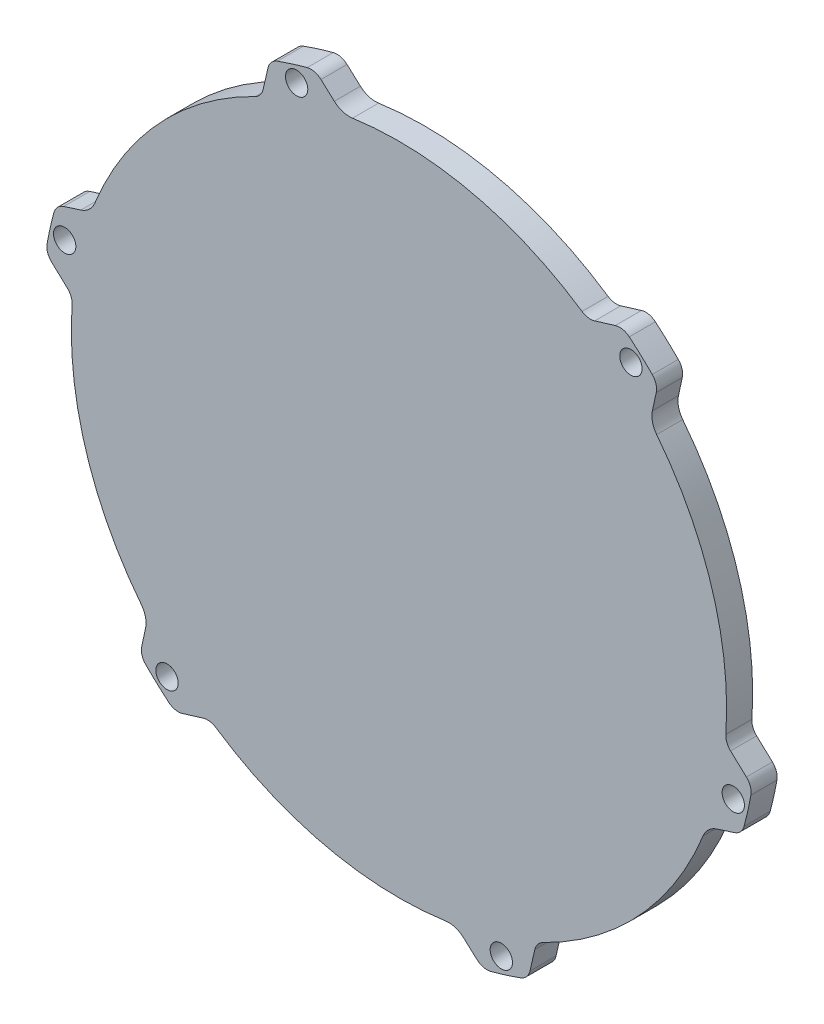
SolidWorks part; units mm, degrees
material "6063-O"
ref_plane "Front Plane" through (0, 0, 0) normal (0, 0, 1) x (1, 0, 0)
ref_plane "Top Plane" through (0, 0, 0) normal (0, 1, 0) x (1, 0, 0)
ref_plane "Right Plane" through (0, 0, 0) normal (1, 0, 0) x (0, 0, -1)
sketch "Sketch2" plane through (0, 0, 0) normal (0, 0, 1) x (1, 0, 0)
  line L0 (-44.8895, 10.0465) -> (-46.8412, 10.4833)
  line L1 (-45.0185, 13.8979) -> (-42.7088, 14.6367)
  line L2 (-46.6479, 6.6175) -> (-44.5268, 4.6417)
  line L4 (-10.4733, 45.9361) -> (-8.6786, 44.3053)
  line L5 (-17.593, 43.707) -> (-18.2436, 40.8822)
  line L7 (34.5452, 32.0382) -> (34.0302, 29.6686)
  line L8 (29.0549, 37.0895) -> (26.2833, 36.2405)
  line L10 (45.0185, -13.8979) -> (42.7088, -14.6367)
  line L11 (46.6479, -6.6175) -> (44.5268, -4.6417)
  line L13 (10.4733, -45.9361) -> (8.6786, -44.3053)
  line L14 (17.593, -43.707) -> (18.2436, -40.8822)
  line L16 (-34.5452, -32.0382) -> (-34.0302, -29.6686)
  line L17 (-29.0549, -37.0895) -> (-26.2833, -36.2405)
  line L18 (-13.7442, 43.8987) -> (-14.3418, 45.8073) [skipped]
  line L19 (31.1453, 33.8522) -> (32.4994, 35.324) [skipped]
  line L20 (44.8895, -10.0465) -> (46.8412, -10.4833) [skipped]
  line L21 (13.7442, -43.8987) -> (14.3418, -45.8073) [skipped]
  line L22 (-31.1453, -33.8522) -> (-32.4994, -35.324) [skipped]
  arc A0 (-46.3399, 12.5144) -> (-47.2535, 8.4323) centre (0, 0) ccw
  arc A1 (-43.8948, 3.0401) -> (-34.6025, -27.1784) centre (0, 0) ccw
  circle A2 centre (-13.7442, 43.8987) radius 1.5
  arc A3 (-40.8384, 16.3775) -> (-42.7088, 14.6367) centre (-43.6229, 17.4941) cw
  arc A4 (-46.6479, 6.6175) -> (-47.2535, 8.4323) centre (-45.2846, 8.081) cw
  arc A5 (-46.3399, 12.5144) -> (-45.0185, 13.8979) centre (-44.4091, 11.993) cw
  arc A6 (-43.8948, 3.0401) -> (-44.5268, 4.6417) centre (-45.8901, 3.1783) ccw
  arc A7 (-12.3322, 46.3888) -> (-16.3242, 45.1389) centre (0, 0) ccw
  arc A8 (-6.2359, 43.5559) -> (-8.6786, 44.3053) centre (-6.6611, 46.5256) cw
  arc A9 (-17.593, 43.707) -> (-16.3242, 45.1389) centre (-15.644, 43.2581) cw
  arc A10 (-12.3322, 46.3888) -> (-10.4733, 45.9361) centre (-11.8183, 44.4559) cw
  arc A11 (-19.3146, 39.5341) -> (-18.2436, 40.8822) centre (-20.1925, 41.3311) ccw
  arc A12 (34.0078, 33.8744) -> (30.9294, 36.7066) centre (0, 0) ccw
  arc A13 (34.6025, 27.1784) -> (34.0302, 29.6686) centre (36.9618, 29.0315) cw
  arc A14 (29.0549, 37.0895) -> (30.9294, 36.7066) centre (29.6406, 35.1772) cw
  arc A15 (34.0078, 33.8744) -> (34.5452, 32.0382) centre (32.5908, 32.4629) cw
  arc A16 (24.5802, 36.494) -> (26.2833, 36.2405) centre (25.6975, 38.1528) ccw
  arc A17 (46.3399, -12.5144) -> (47.2535, -8.4323) centre (0, 0) ccw
  arc A18 (40.8384, -16.3775) -> (42.7088, -14.6367) centre (43.6229, -17.4941) cw
  arc A19 (46.6479, -6.6175) -> (47.2535, -8.4323) centre (45.2846, -8.081) cw
  arc A20 (46.3399, -12.5144) -> (45.0185, -13.8979) centre (44.4091, -11.993) cw
  arc A21 (43.8948, -3.0401) -> (44.5268, -4.6417) centre (45.8901, -3.1783) ccw
  arc A22 (12.3322, -46.3888) -> (16.3242, -45.1389) centre (0, 0) ccw
  arc A23 (6.2359, -43.5559) -> (8.6786, -44.3053) centre (6.6611, -46.5256) cw
  arc A24 (17.593, -43.707) -> (16.3242, -45.1389) centre (15.644, -43.2581) cw
  arc A25 (12.3322, -46.3888) -> (10.4733, -45.9361) centre (11.8183, -44.4559) cw
  arc A26 (19.3146, -39.5341) -> (18.2436, -40.8822) centre (20.1925, -41.3311) ccw
  arc A27 (-34.0078, -33.8744) -> (-30.9294, -36.7066) centre (0, 0) ccw
  arc A28 (-34.6025, -27.1784) -> (-34.0302, -29.6686) centre (-36.9618, -29.0315) cw
  arc A29 (-29.0549, -37.0895) -> (-30.9294, -36.7066) centre (-29.6406, -35.1772) cw
  arc A30 (-34.0078, -33.8744) -> (-34.5452, -32.0382) centre (-32.5908, -32.4629) cw
  arc A31 (-24.5802, -36.494) -> (-26.2833, -36.2405) centre (-25.6975, -38.1528) ccw
  arc A32 (-19.3146, 39.5341) -> (-40.8384, 16.3775) centre (0, 0) ccw
  arc A33 (24.5802, 36.494) -> (-6.2359, 43.5559) centre (0, 0) ccw
  arc A34 (43.8948, -3.0401) -> (34.6025, 27.1784) centre (0, 0) ccw
  arc A35 (19.3146, -39.5341) -> (40.8384, -16.3775) centre (0, 0) ccw
  arc A36 (-24.5802, -36.494) -> (6.2359, -43.5559) centre (0, 0) ccw
  circle A37 centre (-44.8895, 10.0465) radius 1.5
  circle A38 centre (31.1453, 33.8522) radius 1.5
  circle A39 centre (44.8895, -10.0465) radius 1.5
  circle A40 centre (13.7442, -43.8987) radius 1.5
  circle A41 centre (-31.1453, -33.8522) radius 1.5
  circle A42 centre (0, 0) radius 42
  circle A43 centre (0, 0) radius 39.4
  point P15 (-41.3367, 15.0757)
  point P17 (-47.434, 7.3498)
  point P20 (-46.0417, 13.5706)
  point P23 (-43.8194, 3.9827)
  point P93 (0, 0)
  point P105 (0, 0)
  dimension "D1" = 96
  dimension "D2" = 88
  dimension "D3" = 3
  dimension "D4" = 2
  dimension "D5" = 2
  dimension "D7" = 6
  dimension "D8" = 2.6
  dimension "D6" = 6
extrude "Boss-Extrude1" add sketch "Sketch2" along normal blind 2
sketch "Sketch3" plane through (0, 0, 2) normal (0, 0, 1) x (1, 0, 0)
  line L10 (8.6786, -44.3053) -> (10.4733, -45.9361)
  line L12 (-46.6479, 6.6175) -> (-44.5268, 4.6417)
  line L13 (-34.0302, -29.6686) -> (-34.5452, -32.0382)
  line L14 (-29.0549, -37.0895) -> (-26.2833, -36.2405)
  line L15 (8.6786, -44.3053) -> (10.4733, -45.9361)
  line L19 (34.0302, 29.6686) -> (34.5452, 32.0382)
  line L20 (29.0549, 37.0895) -> (26.2833, 36.2405)
  line L21 (-8.6786, 44.3053) -> (-10.4733, 45.9361)
  line L22 (-17.593, 43.707) -> (-18.2436, 40.8822)
  line L23 (-42.7088, 14.6367) -> (-45.0185, 13.8979)
  line L24 (-46.6479, 6.6175) -> (-44.5268, 4.6417)
  line L25 (-34.0302, -29.6686) -> (-34.5452, -32.0382)
  line L26 (-29.0549, -37.0895) -> (-26.2833, -36.2405)
  line L31 (34.0302, 29.6686) -> (34.5452, 32.0382)
  line L32 (29.0549, 37.0895) -> (26.2833, 36.2405)
  line L33 (-8.6786, 44.3053) -> (-10.4733, 45.9361)
  line L34 (-17.593, 43.707) -> (-18.2436, 40.8822)
  line L35 (-42.7088, 14.6367) -> (-45.0185, 13.8979)
  line L36 (17.593, -43.707) -> (18.2436, -40.8822)
  line L37 (17.593, -43.707) -> (18.2436, -40.8822)
  line L38 (42.7088, -14.6367) -> (45.0185, -13.8979)
  line L39 (42.7088, -14.6367) -> (45.0185, -13.8979)
  line L40 (46.6479, -6.6175) -> (44.5268, -4.6417)
  line L41 (46.6479, -6.6175) -> (44.5268, -4.6417)
  arc A26 (8.6786, -44.3053) -> (6.2359, -43.5559) centre (6.6611, -46.5256) ccw
  arc A36 (-45.0185, 13.8979) -> (-46.3399, 12.5144) centre (-44.4091, 11.993) ccw
  arc A37 (-46.3399, 12.5144) -> (-47.2535, 8.4323) centre (0, 0) ccw
  arc A38 (-47.2535, 8.4323) -> (-46.6479, 6.6175) centre (-45.2846, 8.081) ccw
  arc A39 (-43.8948, 3.0401) -> (-44.5268, 4.6417) centre (-45.8901, 3.1783) ccw
  arc A40 (-43.8948, 3.0401) -> (-34.6025, -27.1784) centre (0, 0) ccw
  arc A41 (-34.0302, -29.6686) -> (-34.6025, -27.1784) centre (-36.9618, -29.0315) ccw
  arc A42 (-34.5452, -32.0382) -> (-34.0078, -33.8744) centre (-32.5908, -32.4629) ccw
  arc A43 (-34.0078, -33.8744) -> (-30.9294, -36.7066) centre (0, 0) ccw
  arc A44 (-30.9294, -36.7066) -> (-29.0549, -37.0895) centre (-29.6406, -35.1772) ccw
  arc A45 (-24.5802, -36.494) -> (-26.2833, -36.2405) centre (-25.6975, -38.1528) ccw
  arc A46 (-24.5802, -36.494) -> (6.2359, -43.5559) centre (0, 0) ccw
  arc A49 (8.6786, -44.3053) -> (6.2359, -43.5559) centre (6.6611, -46.5256) ccw
  arc A50 (10.4733, -45.9361) -> (12.3322, -46.3888) centre (11.8183, -44.4559) ccw
  arc A51 (10.4733, -45.9361) -> (12.3322, -46.3888) centre (11.8183, -44.4559) ccw
  arc A52 (12.3322, -46.3888) -> (16.3242, -45.1389) centre (0, 0) ccw
  arc A53 (12.3322, -46.3888) -> (16.3242, -45.1389) centre (0, 0) ccw
  arc A54 (16.3242, -45.1389) -> (17.593, -43.707) centre (15.644, -43.2581) ccw
  arc A55 (16.3242, -45.1389) -> (17.593, -43.707) centre (15.644, -43.2581) ccw
  arc A56 (19.3146, -39.5341) -> (18.2436, -40.8822) centre (20.1925, -41.3311) ccw
  arc A57 (19.3146, -39.5341) -> (18.2436, -40.8822) centre (20.1925, -41.3311) ccw
  arc A58 (43.8948, -3.0401) -> (34.6025, 27.1784) centre (0, 0) ccw
  arc A59 (34.0302, 29.6686) -> (34.6025, 27.1784) centre (36.9618, 29.0315) ccw
  arc A60 (34.5452, 32.0382) -> (34.0078, 33.8744) centre (32.5908, 32.4629) ccw
  arc A61 (34.0078, 33.8744) -> (30.9294, 36.7066) centre (0, 0) ccw
  arc A62 (30.9294, 36.7066) -> (29.0549, 37.0895) centre (29.6406, 35.1772) ccw
  arc A63 (24.5802, 36.494) -> (26.2833, 36.2405) centre (25.6975, 38.1528) ccw
  arc A64 (24.5802, 36.494) -> (-6.2359, 43.5559) centre (0, 0) ccw
  arc A65 (-8.6786, 44.3053) -> (-6.2359, 43.5559) centre (-6.6611, 46.5256) ccw
  arc A66 (-10.4733, 45.9361) -> (-12.3322, 46.3888) centre (-11.8183, 44.4559) ccw
  arc A67 (-12.3322, 46.3888) -> (-16.3242, 45.1389) centre (0, 0) ccw
  arc A68 (-16.3242, 45.1389) -> (-17.593, 43.707) centre (-15.644, 43.2581) ccw
  arc A69 (-19.3146, 39.5341) -> (-18.2436, 40.8822) centre (-20.1925, 41.3311) ccw
  arc A70 (-19.3146, 39.5341) -> (-40.8384, 16.3775) centre (0, 0) ccw
  arc A71 (-42.7088, 14.6367) -> (-40.8384, 16.3775) centre (-43.6229, 17.4941) ccw
  arc A72 (-45.0185, 13.8979) -> (-46.3399, 12.5144) centre (-44.4091, 11.993) ccw
  arc A73 (-46.3399, 12.5144) -> (-47.2535, 8.4323) centre (0, 0) ccw
  arc A74 (-47.2535, 8.4323) -> (-46.6479, 6.6175) centre (-45.2846, 8.081) ccw
  arc A75 (-43.8948, 3.0401) -> (-44.5268, 4.6417) centre (-45.8901, 3.1783) ccw
  arc A76 (-43.8948, 3.0401) -> (-34.6025, -27.1784) centre (0, 0) ccw
  arc A77 (-34.0302, -29.6686) -> (-34.6025, -27.1784) centre (-36.9618, -29.0315) ccw
  arc A78 (-34.5452, -32.0382) -> (-34.0078, -33.8744) centre (-32.5908, -32.4629) ccw
  arc A79 (-34.0078, -33.8744) -> (-30.9294, -36.7066) centre (0, 0) ccw
  arc A80 (-30.9294, -36.7066) -> (-29.0549, -37.0895) centre (-29.6406, -35.1772) ccw
  arc A81 (-24.5802, -36.494) -> (-26.2833, -36.2405) centre (-25.6975, -38.1528) ccw
  arc A82 (-24.5802, -36.494) -> (6.2359, -43.5559) centre (0, 0) ccw
  arc A94 (43.8948, -3.0401) -> (34.6025, 27.1784) centre (0, 0) ccw
  arc A95 (34.0302, 29.6686) -> (34.6025, 27.1784) centre (36.9618, 29.0315) ccw
  arc A96 (34.5452, 32.0382) -> (34.0078, 33.8744) centre (32.5908, 32.4629) ccw
  arc A97 (34.0078, 33.8744) -> (30.9294, 36.7066) centre (0, 0) ccw
  arc A98 (30.9294, 36.7066) -> (29.0549, 37.0895) centre (29.6406, 35.1772) ccw
  arc A99 (24.5802, 36.494) -> (26.2833, 36.2405) centre (25.6975, 38.1528) ccw
  arc A100 (24.5802, 36.494) -> (-6.2359, 43.5559) centre (0, 0) ccw
  arc A101 (-8.6786, 44.3053) -> (-6.2359, 43.5559) centre (-6.6611, 46.5256) ccw
  arc A102 (-10.4733, 45.9361) -> (-12.3322, 46.3888) centre (-11.8183, 44.4559) ccw
  arc A103 (-12.3322, 46.3888) -> (-16.3242, 45.1389) centre (0, 0) ccw
  arc A104 (-16.3242, 45.1389) -> (-17.593, 43.707) centre (-15.644, 43.2581) ccw
  arc A105 (-19.3146, 39.5341) -> (-18.2436, 40.8822) centre (-20.1925, 41.3311) ccw
  arc A106 (-19.3146, 39.5341) -> (-40.8384, 16.3775) centre (0, 0) ccw
  arc A107 (-42.7088, 14.6367) -> (-40.8384, 16.3775) centre (-43.6229, 17.4941) ccw
  circle A108 centre (-13.7442, 43.8987) radius 1.5 construction
  circle A109 centre (-13.7442, 43.8987) radius 1.5
  circle A110 centre (31.1453, 33.8522) radius 1.5 construction
  circle A111 centre (31.1453, 33.8522) radius 1.5
  circle A112 centre (-44.8895, 10.0465) radius 1.5 construction
  circle A113 centre (-44.8895, 10.0465) radius 1.5
  circle A114 centre (-31.1453, -33.8522) radius 1.5 construction
  circle A115 centre (-31.1453, -33.8522) radius 1.5
  circle A116 centre (13.7442, -43.8987) radius 1.5 construction
  circle A117 centre (13.7442, -43.8987) radius 1.5
  circle A118 centre (44.8895, -10.0465) radius 1.5 construction
  circle A119 centre (44.8895, -10.0465) radius 1.5
  arc A120 (19.3146, -39.5341) -> (40.8384, -16.3775) centre (0, 0) ccw
  arc A121 (19.3146, -39.5341) -> (40.8384, -16.3775) centre (0, 0) ccw
  arc A122 (42.7088, -14.6367) -> (40.8384, -16.3775) centre (43.6229, -17.4941) ccw
  arc A123 (42.7088, -14.6367) -> (40.8384, -16.3775) centre (43.6229, -17.4941) ccw
  arc A124 (45.0185, -13.8979) -> (46.3399, -12.5144) centre (44.4091, -11.993) ccw
  arc A125 (45.0185, -13.8979) -> (46.3399, -12.5144) centre (44.4091, -11.993) ccw
  arc A126 (46.3399, -12.5144) -> (47.2535, -8.4323) centre (0, 0) ccw
  arc A127 (46.3399, -12.5144) -> (47.2535, -8.4323) centre (0, 0) ccw
  arc A128 (47.2535, -8.4323) -> (46.6479, -6.6175) centre (45.2846, -8.081) ccw
  arc A129 (47.2535, -8.4323) -> (46.6479, -6.6175) centre (45.2846, -8.081) ccw
  arc A130 (43.8948, -3.0401) -> (44.5268, -4.6417) centre (45.8901, -3.1783) ccw
  arc A131 (43.8948, -3.0401) -> (44.5268, -4.6417) centre (45.8901, -3.1783) ccw
  dimension "D1" = 0
extrude "Boss-Extrude2" add sketch "Sketch3" along normal blind 1.5
sketch "Sketch4" plane through (0, 0, 0) normal (0, 0, -1) x (-1, 0, 0)
  circle A0 centre (0, 0) radius 37
extrude "Cut-Extrude1" cut sketch "Sketch4" against normal up to surface (2 mm away) contours A0 up to face at (39.4, 0, 2)
